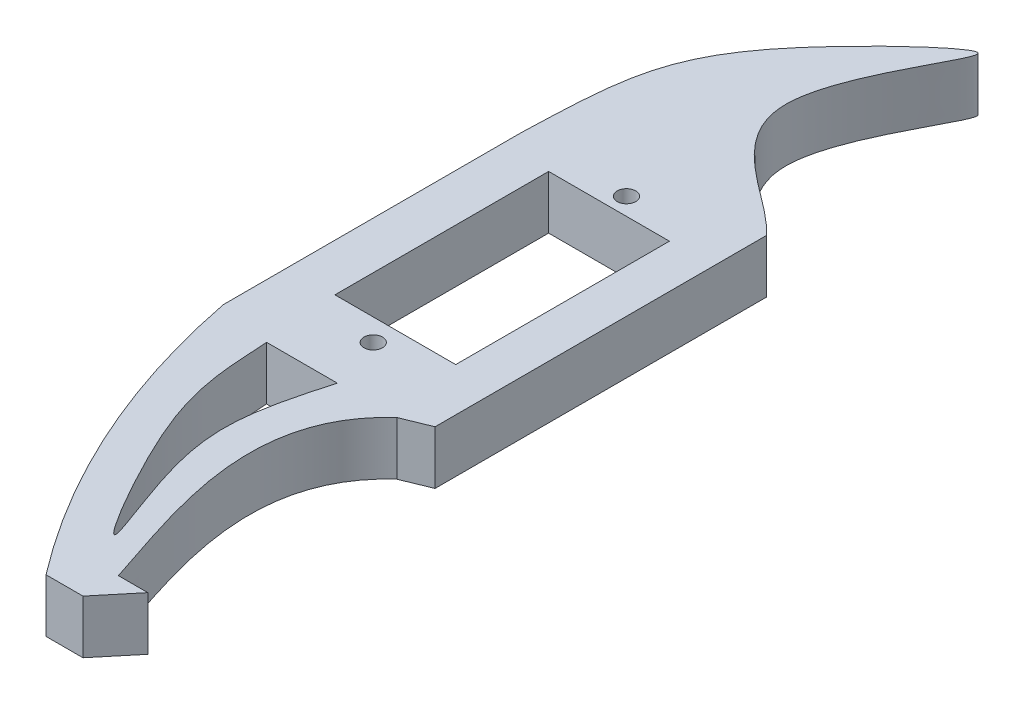
SolidWorks part; units mm, degrees
ref_plane "Front Plane" through (0, 0, 0) normal (0, 0, 1) x (1, 0, 0)
ref_plane "Top Plane" through (0, 0, 0) normal (0, 1, 0) x (1, 0, 0)
ref_plane "Right Plane" through (0, 0, 0) normal (1, 0, 0) x (0, 0, -1)
sketch "Sketch2" plane through (0, 0, 0) normal (0, 1, 0) x (1, 0, 0)
  line L0 (91.748, 286.1056) -> (91.748, 162.0938)
  line L1 (91.748, 162.0938) -> (81.6032, 157.9436)
  line L2 (12.5257, 273.6909) -> (12.5257, 162.0938)
  line L3 (80.7375, 54.5688) -> (91.748, 54.5688)
  line L4 (66.9019, 41.3155) -> (80.7375, 41.3155)
  line L5 (32.8418, 157.9436) -> (59.2885, 157.9436)
  line L6 (52.8418, 295.8774) -> (52.8418, 166.8638) construction
  line L7 (22.3319, 226.1168) -> (82.9041, 226.1168) construction
  line L47 (32.8418, 266.1168) -> (72.8418, 266.1168)
  line L48 (72.8418, 266.1168) -> (72.8418, 186.1168)
  line L49 (72.8418, 186.1168) -> (32.8418, 186.1168)
  line L50 (32.8418, 186.1168) -> (32.8418, 266.1168)
  spline S0 degree 3 poles (91.748, 286.1056) (79.9224, 299.3552) (28.2597, 319.4576) (93.2574, 407.7691) (14.4879, 335.7329) (13.835, 311.3595) (12.5257, 273.6909) knots 0 0 0 0 0.243536 0.469286 0.650564 1 1 1 1
  spline S1 degree 3 poles (81.6032, 157.9436) (51.4898, 130.8831) (71.0774, 84.6764) (80.7375, 54.5688) knots 0 0 0 0 1 1 1 1
  spline S2 degree 2 poles (12.5257, 162.0938) (25.627, 95.3501) (66.9019, 41.3155) knots 0 0 0 1 1 1
  spline S3 degree 1 poles (91.748, 54.5688) (80.7375, 41.3155) knots 0 0 1 1
  spline S4 degree 3 poles (59.2885, 157.9436) (52.906, 134.6588) (47.7304, 114.953) (77.2171, 45.9033) (34.9072, 118.0374) (33.7939, 140.225) (32.8418, 157.9436) knots 0 0 0 0 0.317344 0.486949 0.743913 1 1 1 1
  point P22 (0, 0)
  dimension "D1" = 80
extrude "Boss-Extrude1" add sketch "Sketch2" along normal blind 20
scale "Scale1" bodies to scale 101 scale about origin uniform scaling yes scale factor 0.2875
sketch "Çizim1" plane through (0, 5.75, 0) normal (0, 1, 0) x (1, 0, 0)
  line L0 (20.942, 76.5086) -> (21.692, 76.5086)
  line L1 (21.692, 76.5086) -> (21.692, 53.5086)
  line L2 (9.442, 76.5086) -> (8.692, 76.5086)
  line L3 (8.692, 76.5086) -> (8.692, 53.5086)
  line L4 (8.692, 53.5086) -> (9.442, 53.5086)
  line L5 (20.942, 53.5086) -> (21.692, 53.5086)
  line L6 (20.942, 53.5086) -> (20.942, 76.5086) construction
  line L7 (20.942, 53.5086) -> (20.942, 76.5086)
  line M1 (9.442, 53.5086) -> (9.442, 76.5086)
  dimension "D1" = 0.75
  dimension "D2" = 0.75
extrude "Kes-Ekstrüzyon1" cut sketch "Çizim1" against normal up to next contours L3 L4 L2 M1 | L7 L0 L1 L5
sketch "Çizim3" plane through (0, 5.75, 0) normal (0, 1, 0) x (1, 0, 0)
  circle A0 centre (15.192, 51.1336) radius 1
  circle A1 centre (15.192, 78.3836) radius 1
extrude "Kes-Ekstrüzyon2" cut sketch "Çizim3" against normal up to next
